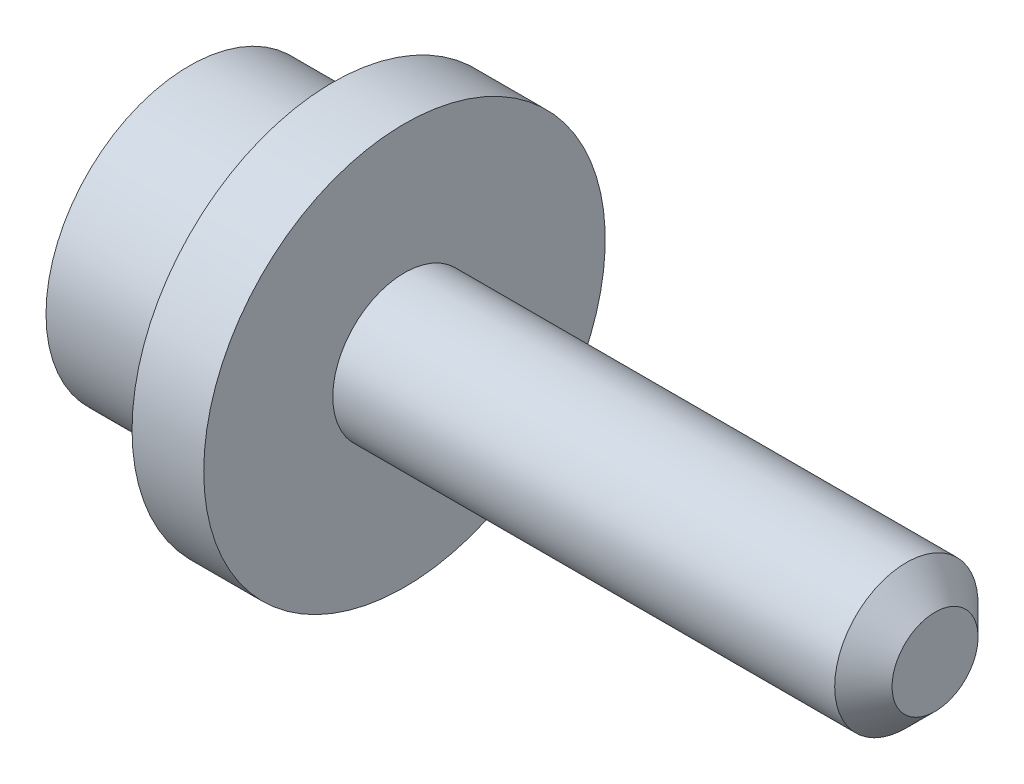
SolidWorks part; units mm, degrees
material "Acier non allié"
ref_plane "Plan de face" through (0, 0, 0) normal (0, 0, 1) x (1, 0, 0)
ref_plane "Plan de dessus" through (0, 0, 0) normal (0, 1, 0) x (1, 0, 0)
ref_plane "Plan de droite" through (0, 0, 0) normal (1, 0, 0) x (0, 0, -1)
sketch "Esquisse1" plane through (0, 0, 0) normal (0, 0, 1) x (1, 0, 0)
  line L0 (0, 1.5) -> (15, 1.5)
  line L1 (-19.1632, 0) -> (84.4478, 0) construction
  line L2 (7.5, 7) -> (5, 7)
  line L3 (5, 7) -> (5, 5)
  line L4 (5, 5) -> (0, 5)
  line L5 (0, 5) -> (0, 1.5)
  line L6 (15, 1.5) -> (15, 0)
  line L7 (15, 0) -> (26, 0)
  line L8 (26, 0) -> (26, 2.5)
  line L9 (26, 2.5) -> (7.5, 2.5)
  line L10 (7.5, 2.5) -> (7.5, 7)
  dimension "D1" = 2.5
  dimension "D2" = 1.5
  dimension "D3" = 5
  dimension "D4" = 7
  dimension "D5" = 5
  dimension "D6" = 7.5
  dimension "D7" = 26
  dimension "D8" = 15
revolve "Révolution1" add sketch "Esquisse1" angle 360 about L1
chamfer "Chanfrein1" distance 1 angle 45 1 edges at (26, 0, 2.5)
